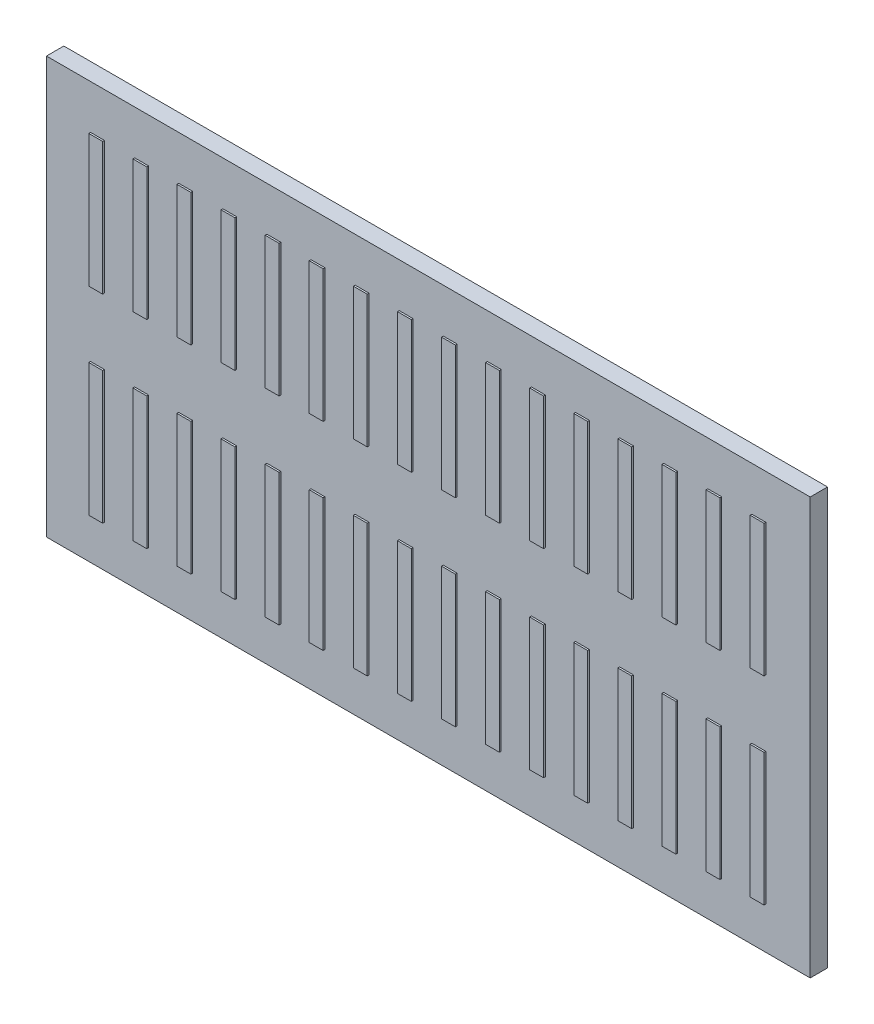
SolidWorks part; units mm, degrees
material "Silicon"
ref_plane "Front Plane" through (0, 0, 0) normal (0, 0, 1) x (1, 0, 0)
ref_plane "Top Plane" through (0, 0, 0) normal (0, 1, 0) x (1, 0, 0)
ref_plane "Right Plane" through (0, 0, 0) normal (1, 0, 0) x (0, 0, -1)
sketch "Sketch1" plane through (0, 0, 0) normal (0, 0, 1) x (1, 0, 0)
  line L1 (0, 0) -> (110, 0)
  line L2 (0, 0) -> (0, 60)
  line L3 (0, 60) -> (110, 60)
  line L4 (110, 0) -> (110, 60)
  dimension "D1" = 110
  dimension "D2" = 60
extrude "Boss-Extrude1" add sketch "Sketch1" along normal blind 2.5
sketch "Sketch3" plane through (0, 0, 2.5) normal (0, 0, 1) x (1, 0, 0)
  line L0 (0, 60) -> (0, 0) construction
  line L1 (6.35, 53.65) -> (8.35, 53.65)
  line L2 (6.35, 53.65) -> (6.35, 34.6)
  line L3 (6.35, 34.6) -> (8.35, 34.6)
  line L4 (8.35, 53.65) -> (8.35, 34.6)
  line L5 (110, 60) -> (0, 60) construction
  dimension "D1" = 2
  dimension "D2" = 6.35
  dimension "D3" = 6.35
  dimension "D4" = 19.05
extrude "Boss-Extrude2" add sketch "Sketch3" along normal blind 0.254
pattern_linear "LPattern1" count 16 spacing 6.35 along (1, 0, 0) count 2 spacing 28.575 along (0, -1, 0) of "Boss-Extrude2"
